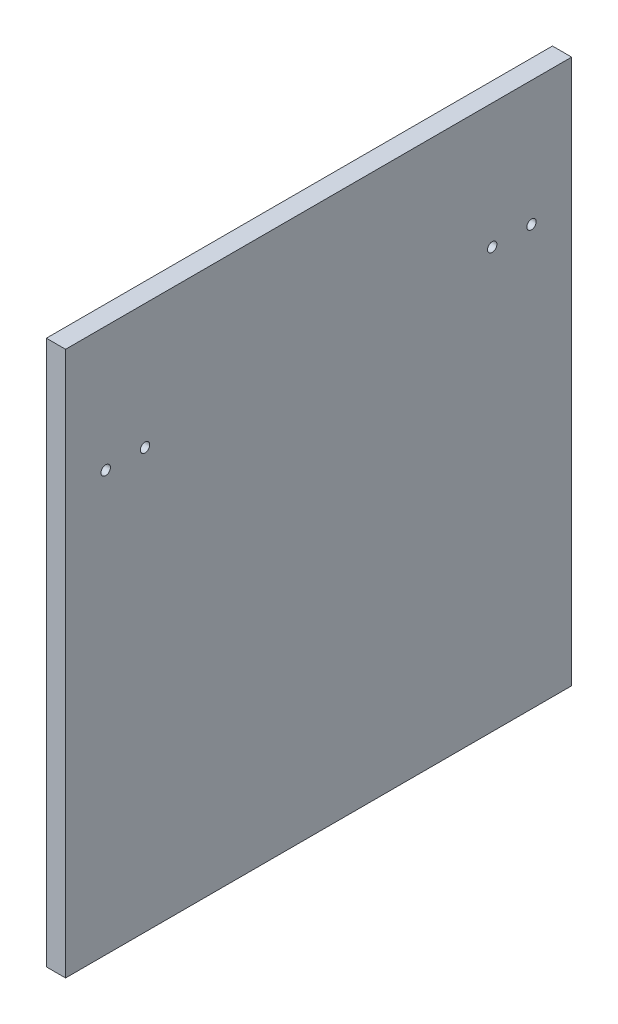
SolidWorks part; units mm, degrees
ref_plane "Front Plane" through (0, 0, 0) normal (0, 0, 1) x (1, 0, 0)
ref_plane "Top Plane" through (0, 0, 0) normal (0, 1, 0) x (1, 0, 0)
ref_plane "Right Plane" through (0, 0, 0) normal (1, 0, 0) x (0, 0, -1)
sketch "Sketch1" plane through (0, 0, 0) normal (1, 0, 0) x (0, 0, -1)
  line L1 (83.65, -90) -> (-83.65, -90)
  line L2 (83.65, -90) -> (83.65, 90)
  line L3 (83.65, 90) -> (-83.65, 90)
  line L4 (-83.65, -90) -> (-83.65, 90)
  line L5 (83.65, -90) -> (-83.65, 90) construction
  line L6 (83.65, 90) -> (-83.65, -90) construction
  point P0 (0, 0)
  dimension "D1" = 167.3
  dimension "D2" = 180
extrude "Boss-Extrude1" add sketch "Sketch1" along normal blind 6.35
sketch "Sketch2" plane through (0, 0, 0) normal (-1, 0, 0) x (0, 0, 1)
  line L0 (-63.883, 60) -> (63.883, 60) construction
  line L1 (-83.65, 90) -> (83.65, 90) construction
  line L2 (70.378, 48.7497) -> (-70.378, 48.7497) construction
  line L3 (83.65, 90) -> (83.65, -90) construction
  circle A0 centre (-63.883, 60) radius 1.55 construction
  circle A1 centre (63.883, 60) radius 1.55 construction
  circle A2 centre (57.3873, 48.7497) radius 1.55
  circle A3 centre (70.378, 48.7497) radius 1.55
  circle A4 centre (-57.3879, 48.7497) radius 1.55
  circle A5 centre (-70.378, 48.7497) radius 1.55
  point P2 (0, 60)
  point P3 (0, 90)
  point P10 (0, 48.7497)
  dimension "D1" = 3.1
  dimension "D2" = 127.7661
  dimension "D3" = 30
  dimension "D4" = 140.7559
  dimension "D5" = 114.7752
  dimension "D7" = 41.2503
  dimension "D8" = 26.2627
extrude "Cut-Extrude1" cut sketch "Sketch2" against normal through all
